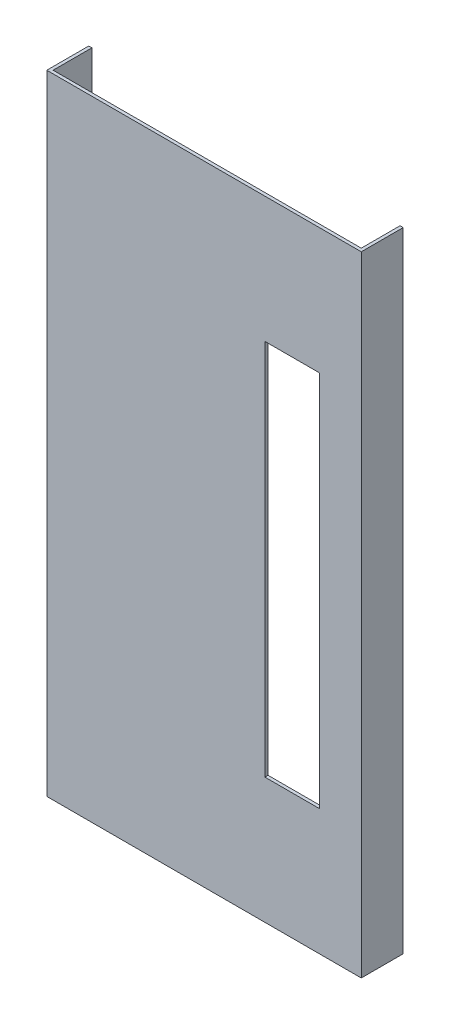
SolidWorks part; units mm, degrees
ref_plane "Front Plane" through (0, 0, 0) normal (0, 0, 1) x (1, 0, 0)
ref_plane "Top Plane" through (0, 0, 0) normal (0, 1, 0) x (1, 0, 0)
ref_plane "Right Plane" through (0, 0, 0) normal (1, 0, 0) x (0, 0, -1)
other "Configuration Table"
sketch "Sketch1" plane through (0, 0, 0) normal (0, 1, 0) x (1, 0, 0)
  line L0 (30, -40) -> (30, -20)
  line L1 (30, -20) -> (31.5, -20)
  line L2 (31.5, -20) -> (31.5, -38.5)
  line L3 (31.5, -38.5) -> (178.5, -38.5)
  line L4 (178.5, -38.5) -> (178.5, -20)
  line L5 (178.5, -20) -> (180, -20)
  line L6 (180, -20) -> (180, -40)
  line L7 (180, -40) -> (30, -40)
extrude "OVEN_yag_kabi_kapagi_kapak_1" add sketch "Sketch1" along normal blind 300 from offset 820 separate body
sketch "Sketch2" plane through (0, 0, 0) normal (0, 0, 1) x (1, 0, 0)
  line L1 (134, 880) -> (160, 880)
  line L2 (134, 880) -> (134, 1060)
  line L3 (134, 1060) -> (160, 1060)
  line L4 (160, 880) -> (160, 1060)
extrude "OVEN_yag_kabi_kapagi_kapak_2" cut sketch "Sketch2" along normal blind 14 from offset 27
